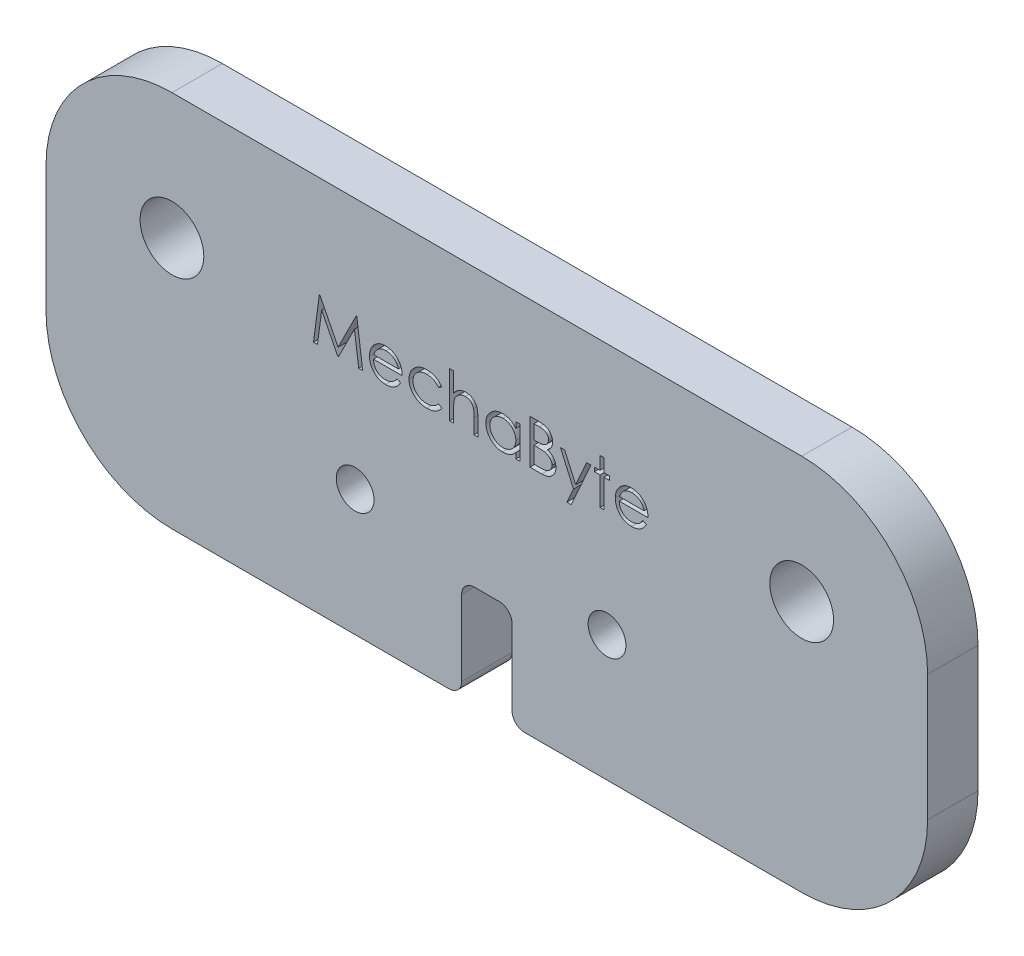
SolidWorks part; units mm, degrees
ref_plane "Front Plane" through (0, 0, 0) normal (0, 0, 1) x (1, 0, 0)
ref_plane "Top Plane" through (0, 0, 0) normal (0, 1, 0) x (1, 0, 0)
ref_plane "Right Plane" through (0, 0, 0) normal (1, 0, 0) x (0, 0, -1)
sketch "Sketch1" plane through (0, 0, 0) normal (0, 0, 1) x (1, 0, 0)
  line L0 (-37, 1) -> (-37, 7)
  line L1 (-10, 0) -> (-32, 0)
  line L2 (0, 10) -> (0, 20)
  line L3 (-10, 30) -> (-60, 30)
  line L4 (-70, 10) -> (-70, 20)
  line L8 (-38, 0) -> (-60, 0)
  line L9 (-33, 1) -> (-33, 7)
  line L10 (-34, 8) -> (-36, 8)
  circle A0 centre (-25.4563, 10) radius 1.5
  circle A1 centre (-45.4563, 10) radius 1.5
  arc A2 (-70, 10) -> (-60, 0) centre (-60, 10) ccw
  arc A3 (-10, 0) -> (0, 10) centre (-10, 10) ccw
  arc A4 (-70, 20) -> (-60, 30) centre (-60, 20) cw
  arc A5 (0, 20) -> (-10, 30) centre (-10, 20) ccw
  arc A6 (-34, 8) -> (-33, 7) centre (-34, 7) cw
  arc A7 (-37, 7) -> (-36, 8) centre (-36, 7) cw
  arc A8 (-38, 0) -> (-37, 1) centre (-38, 1) ccw
  arc A9 (-32, 0) -> (-33, 1) centre (-32, 1) cw
  circle A10 centre (-10, 20) radius 2.53
  circle A11 centre (-60, 20) radius 2.53
  point P13 (0, 0)
  point P28 (-37, 0)
  dimension "D1" = 10
  dimension "D2" = 1
  dimension "D3" = 1
extrude "Boss-Extrude1" add sketch "Sketch1" along normal blind 4
sketch "Sketch2" plane through (0, 0, 4) normal (0, 0, 1) x (1, 0, 0)
  text T0 "MechaByte"
extrude "Cut-Extrude1" cut sketch "Sketch2" against normal through all
